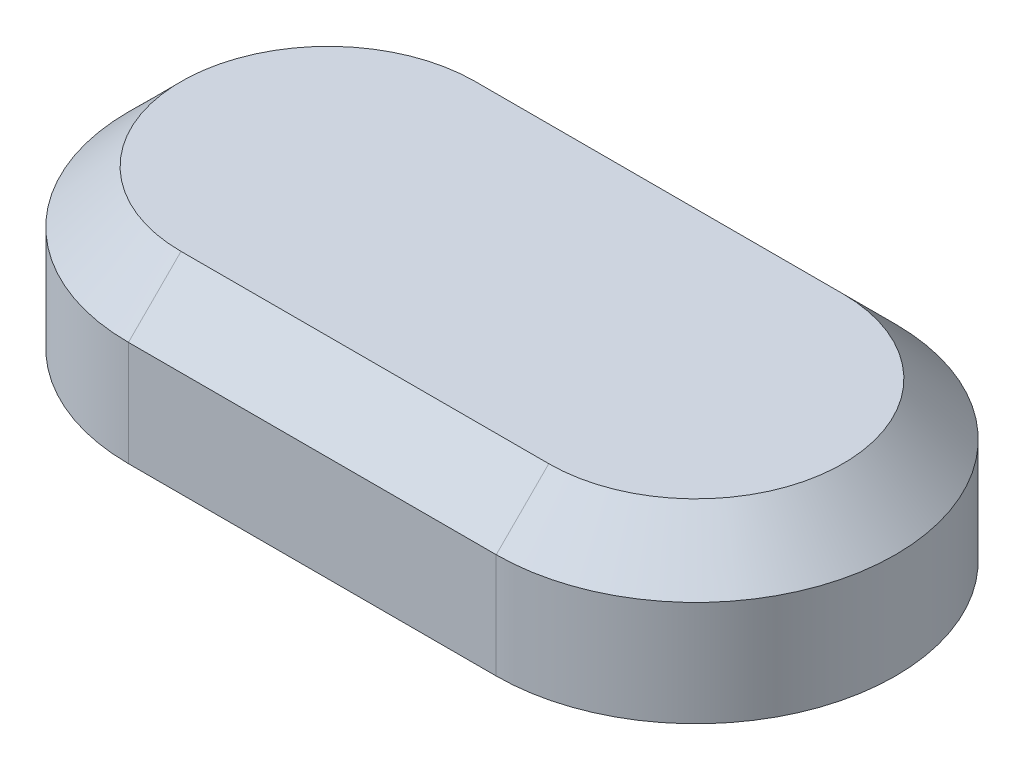
SolidWorks part; units mm, degrees
ref_plane "Plan de face" through (0, 0, 0) normal (0, 0, 1) x (1, 0, 0)
ref_plane "Plan de dessus" through (0, 0, 0) normal (0, 1, 0) x (1, 0, 0)
ref_plane "Plan de droite" through (0, 0, 0) normal (1, 0, 0) x (0, 0, -1)
sketch "Esquisse1" plane through (0, 0, 0) normal (0, 1, 0) x (1, 0, 0)
  line L0 (-3.5, 0) -> (3.5, 0) construction
  line L1 (-3.5, 3.8) -> (3.5, 3.8)
  line L2 (-3.5, -3.8) -> (3.5, -3.8)
  arc A0 (-3.5, 3.8) -> (-3.5, -3.8) centre (-3.5, 0) ccw
  arc A1 (3.5, -3.8) -> (3.5, 3.8) centre (3.5, 0) ccw
  point P2 (0, 0)
  point P7 (-7.3, 0)
  point P8 (7.3, 0)
  dimension "D1" = 7.6
  dimension "D2" = 14.6
extrude "Boss.-Extru.1" add sketch "Esquisse1" along normal blind 3
chamfer "Chanfrein1" distance 1 angle 45 4 edges at (-7.3, 3, 0) (0, 3, -3.8) (7.3, 3, 0) (0, 3, 3.8)
